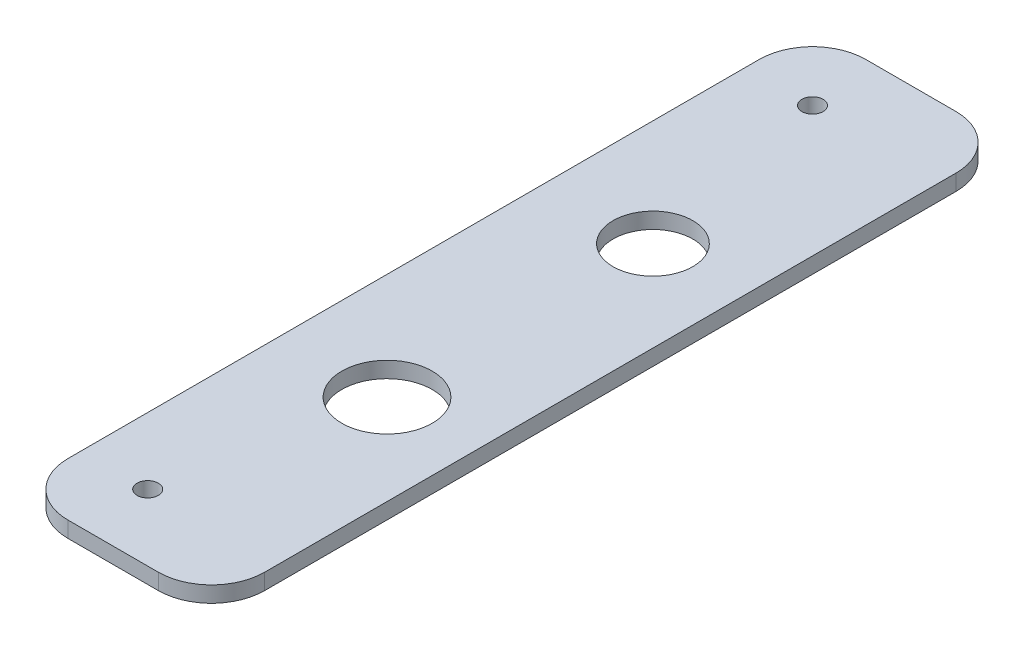
SolidWorks part; units mm, degrees
ref_plane "Alzado" through (0, 0, 0) normal (0, 0, 1) x (1, 0, 0)
ref_plane "Planta" through (0, 0, 0) normal (0, 1, 0) x (1, 0, 0)
ref_plane "Vista lateral" through (0, 0, 0) normal (1, 0, 0) x (0, 0, -1)
sketch "Croquis1" plane through (0, 0, 0) normal (0, 1, 0) x (1, 0, 0)
  line L1 (-18.5, 75) -> (18.5, 75)
  line L2 (-18.5, 75) -> (-18.5, -75)
  line L3 (-18.5, -75) -> (18.5, -75)
  line L4 (18.5, 75) -> (18.5, -75)
  line L5 (-18.5, 75) -> (18.5, -75) construction
  line L6 (-18.5, -75) -> (18.5, 75) construction
  circle A0 centre (1.5, 25) radius 7.5
  circle A1 centre (1.5, -25) radius 8.5
  point P0 (0, 0)
  dimension "D3" = 15
  dimension "D4" = 17
  dimension "D5" = 20
  dimension "D6" = 20
  dimension "D7" = 50
  dimension "D8" = 50
  dimension "D1" = 37
  dimension "D2" = 150
extrude "Saliente-Extruir1" add sketch "Croquis1" along normal blind 3
fillet "Redondeo1" radius 10 4 edges at (-18.5, 1.5, -75) (18.5, 1.5, -75) (-18.5, 1.5, 75) (18.5, 1.5, 75)
sketch "Croquis2" plane through (0, 3, 0) normal (0, 1, 0) x (1, 0, 0)
  line L0 (8.5, 75) -> (-8.5, 75) construction
  line L1 (-18.5, 65) -> (-18.5, -65) construction
  line L2 (-8.5, -75) -> (8.5, -75) construction
  circle A0 centre (-6, 62.5) radius 2
  circle A1 centre (-6, -62.5) radius 2
  dimension "D1" = 4
  dimension "D2" = 4
  dimension "D3" = 12.5
  dimension "D4" = 12.5
  dimension "D6" = 12.5
  dimension "D5" = 12.5
extrude "Cortar-Extruir1" cut sketch "Croquis2" against normal blind 10
